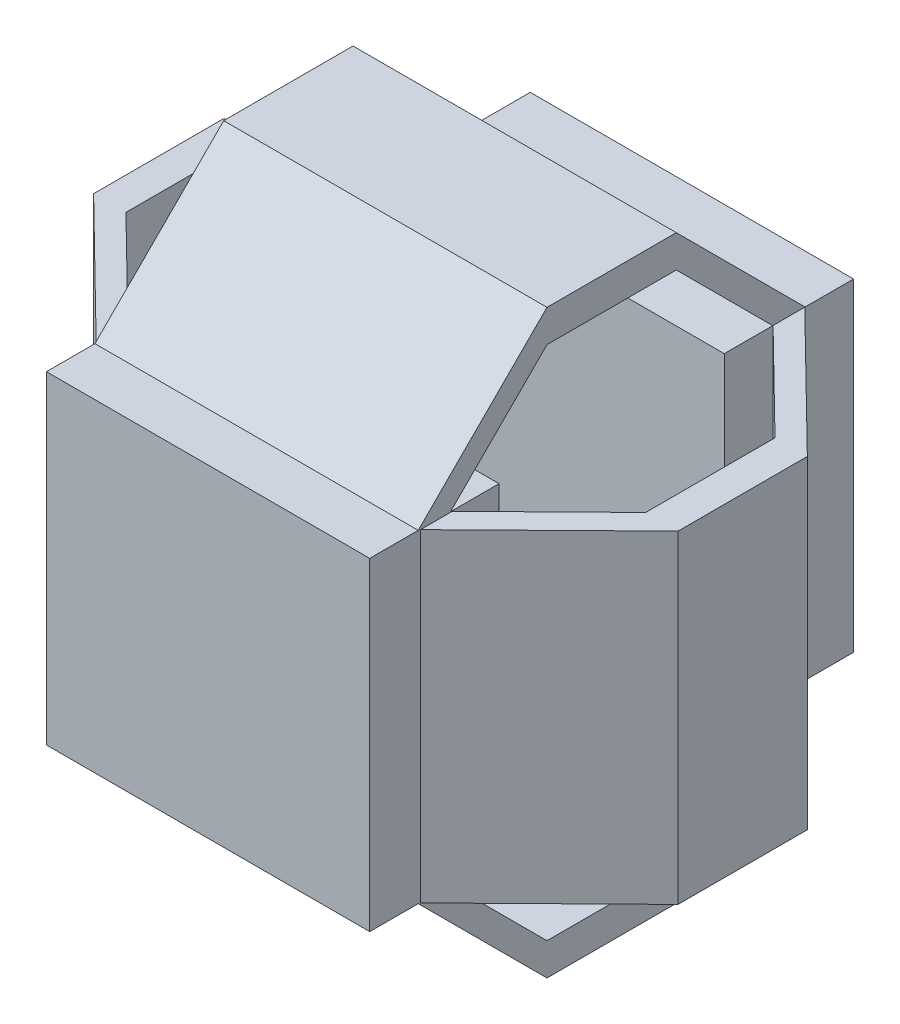
SolidWorks part; units mm, degrees
ref_plane "Front Plane" through (0, 0, 0) normal (0, 0, 1) x (1, 0, 0)
ref_plane "Top Plane" through (0, 0, 0) normal (0, 1, 0) x (1, 0, 0)
ref_plane "Right Plane" through (0, 0, 0) normal (1, 0, 0) x (0, 0, -1)
sketch "Sketch2" plane through (0, 0, 0) normal (0, 0, 1) x (1, 0, 0)
  line L1 (-2.5, 2.5) -> (2.5, 2.5)
  line L2 (-2.5, 2.5) -> (-2.5, -2.5)
  line L3 (-2.5, -2.5) -> (2.5, -2.5)
  line L4 (2.5, 2.5) -> (2.5, -2.5)
  line L5 (-2.5, 2.5) -> (2.5, -2.5) construction
  line L6 (-2.5, -2.5) -> (2.5, 2.5) construction
  point P0 (0, 0)
  dimension "D1" = 5
  dimension "D2" = 5
extrude "Boss-Extrude1" add sketch "Sketch2" along normal blind 2
sketch "Sketch4" plane through (2.5, 0, 0) normal (1, 0, 0) x (0, 0, -1)
  line L0 (-1, -2.5) -> (-1, -3.8362) construction
  line L1 (-2, -2.5) -> (0, -2.5) construction
  line L2 (-1, -2.5) -> (-2.5586, -2.5) construction
  line L3 (-1.25, -2.5) -> (-2.7415, -3.9915)
  line L4 (-2.7415, -3.9915) -> (-2.7415, -4.4915)
  line L5 (-2.7415, -4.4915) -> (-0.75, -2.5)
  line L6 (-0.75, -2.5) -> (-1.25, -2.5)
  point P9 (-1, -2.5)
  dimension "D1" = 0.5
  dimension "D2" = 0.5
  dimension "D3" = 0.3536
extrude "Boss-Extrude3" add sketch "Sketch4" against normal blind 5
sketch "Sketch9" plane through (0, 2.5, 0) normal (0, 1, 0) x (1, 0, 0)
  line L1 (2.5, -2) -> (2.5, 0) construction
  line L2 (2.5, -0.755) -> (4.5193, -2.7343)
  line L3 (4.5193, -2.7343) -> (4.0193, -2.7343)
  line L4 (4.0193, -2.7343) -> (2.5, -1.245)
  line L6 (2.5, -2.7415) -> (5.5161, -2.7415) construction
  line L7 (2.5, -0.755) -> (2.5, -1.245)
  point P0 (2.5, -1)
  point P10 (2.5, -1)
  dimension "D1" = 0.35
  dimension "D2" = 0.5
  dimension "D4" = 0.4901
extrude "Boss-Extrude4" add sketch "Sketch9" against normal blind 5
mirror "Mirror2" about plane through (0, 0, 0) normal (0, 1, 0) of "Boss-Extrude3"
mirror "Mirror3" about plane through (0, 0, 0) normal (1, 0, 0) of "Boss-Extrude4"
sketch "Sketch10" plane through (0, 0, 2.7343) normal (0, 0, 1) x (1, 0, 0)
  line L0 (-4.5193, 2.5) -> (-4.0193, 2.5)
  line L1 (-4.0193, 2.5) -> (-4.0193, -2.5)
  line L2 (-4.0193, -2.5) -> (-4.5193, -2.5)
  line L3 (-4.5193, -2.5) -> (-4.5193, 2.5)
sketch "Sketch11" plane through (0, 0, 2.7415) normal (0, 0, 1) x (1, 0, 0)
  line L0 (-2.5, -3.9915) -> (2.5, -3.9915)
  line L1 (2.5, -3.9915) -> (2.5, -4.4915)
  line L2 (2.5, -4.4915) -> (-2.5, -4.4915)
  line L3 (-2.5, -4.4915) -> (-2.5, -3.9915)
sketch "Sketch12" plane through (0, 0, 2.7415) normal (0, 0, 1) x (1, 0, 0)
  line L0 (-2.5, -3.9915) -> (-2.5, -4.4915)
  line L1 (-2.5, -4.4915) -> (2.5, -4.4915)
  line L2 (2.5, -4.4915) -> (2.5, -3.9915)
  line L3 (2.5, -3.9915) -> (-2.5, -3.9915)
extrude "Boss-Extrude5" add sketch "Sketch12" along normal blind 1
sketch "Sketch13" plane through (0, 0, 2.7343) normal (0, 0, 1) x (1, 0, 0)
  line L0 (4.0193, 2.5) -> (4.5193, 2.5)
  line L1 (4.5193, 2.5) -> (4.5193, -2.5)
  line L2 (4.5193, -2.5) -> (4.0193, -2.5)
  line L3 (4.0193, -2.5) -> (4.0193, 2.5)
extrude "Boss-Extrude6" add sketch "Sketch13" along normal blind 1
mirror "Mirror4" about plane through (0, 0, 0) normal (0, 1, 0) of "Boss-Extrude5"
mirror "Mirror5" about plane through (0, 0, 0) normal (1, 0, 0) of "Boss-Extrude6"
ref_plane "Plane1" through (0, 0, 3.7415) normal (0, 0, 1) x (1, 0, 0)
mirror "Mirror8" about plane through (0, 0, 3.7415) normal (0, 0, 1) of "Mirror4", "Boss-Extrude5"
mirror "Mirror9" about plane through (0, 0, 3.7415) normal (0, 0, 1) of "Mirror2", "Boss-Extrude3"
ref_plane "Plane2" through (0, 0, 3.7343) normal (0, 0, 1) x (1, 0, 0)
mirror "Mirror14" about plane through (0, 0, 3.7343) normal (0, 0, 1) of "Mirror5", "Boss-Extrude6"
sketch "Sketch14" plane through (0, -2.5, 0) normal (0, -1, 0) x (1, 0, 0)
  line L0 (4.5193, 4.7343) -> (4.0193, 4.7343)
  line L1 (4.0193, 4.7343) -> (2.5081, 6.2156)
  line L2 (2.5081, 6.2156) -> (2.5081, 6.7057)
  line L3 (2.5081, 6.7057) -> (4.5193, 4.7343)
  dimension "D1" = 0.35
extrude "Boss-Extrude7" add sketch "Sketch14" against normal blind 5
mirror "Mirror15" about plane through (0, 0, 0) normal (1, 0, 0) of "Boss-Extrude7"
mirror "Mirror16" about plane through (0, 0, 3.7415) normal (0, 0, 1) of "Boss-Extrude1"
